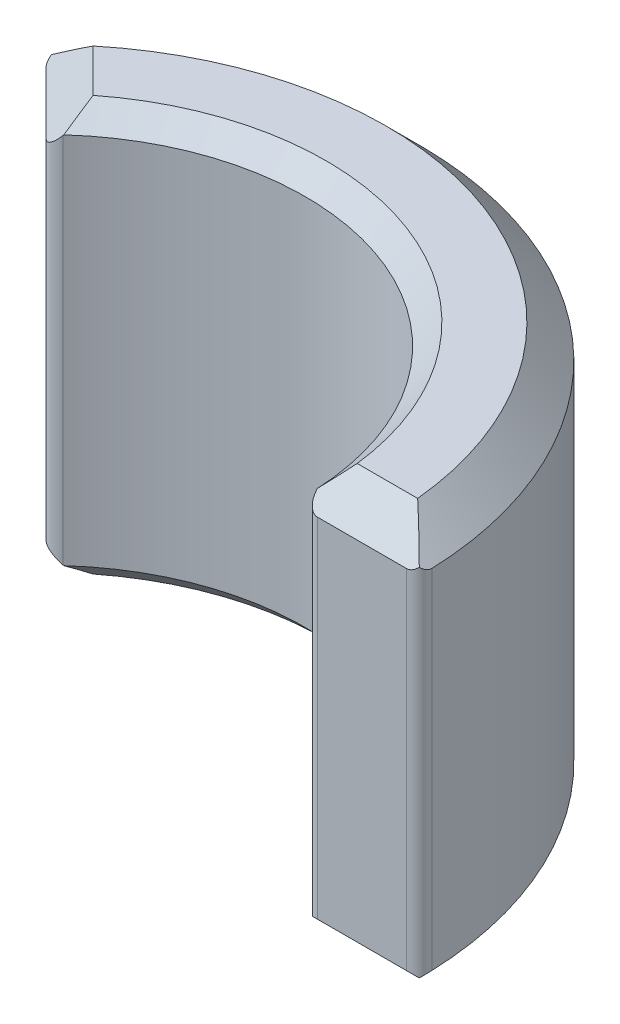
SolidWorks part; units mm, degrees
material "Ferrite"
ref_plane "Front Plane" through (0, 0, 0) normal (0, 0, 1) x (1, 0, 0)
ref_plane "Top Plane" through (0, 0, 0) normal (0, 1, 0) x (1, 0, 0)
ref_plane "Right Plane" through (0, 0, 0) normal (1, 0, 0) x (0, 0, -1)
sketch "Sketch1" plane through (0, 0, 0) normal (0, 1, 0) x (1, 0, 0)
  line L0 (0, 0) -> (11.43, 0)
  line L1 (0, 0) -> (-8.0822, 8.0822)
  circle A0 centre (0, 0) radius 7.9375
  circle A1 centre (0, 0) radius 11.43
  dimension "D1" = 15.875
  dimension "D2" = 22.86
  dimension "D3" = 135
extrude "Boss-Extrude1" add sketch "Sketch1" along normal blind 12.7 contours L0 A1 L1 A0
chamfer "Chamfer1" distance 1.016 angle 45 6 edges at (-6.8474, 0, -6.8474) (9.6837, 0, 0) (4.3741, 0, -10.5599) (9.6837, 12.7, 0) (-6.8474, 12.7, -6.8474) (4.3741, 12.7, -10.5599)
chamfer "Chamfer2" distance 0.635 angle 45 2 edges at (3.0375, 0, -7.3333) (3.0375, 12.7, -7.3333)
fillet "Fillet1" radius 0.381 4 edges at (7.9375, 6.35, 0) (11.43, 6.35, 0) (-8.0822, 6.35, -8.0822) (-5.6127, 6.35, -5.6127)
